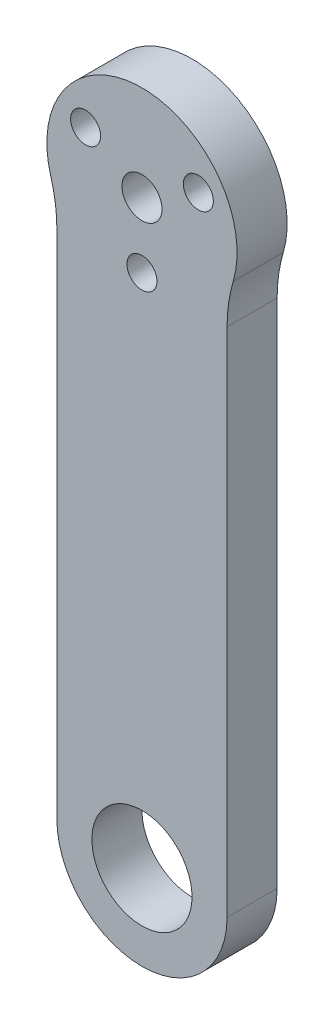
SolidWorks part; units mm, degrees
material "Thornel Mat VMA"
ref_plane "前视基准面" through (0, 0, 0) normal (0, 0, 1) x (1, 0, 0)
ref_plane "上视基准面" through (0, 0, 0) normal (0, 1, 0) x (1, 0, 0)
ref_plane "右视基准面" through (0, 0, 0) normal (1, 0, 0) x (0, 0, -1)
sketch "草图1" plane through (0, 0, 0) normal (0, 0, 1) x (1, 0, 0)
  line L0 (0, 0) -> (0, -58) construction
  line L1 (-8.5, -58) -> (-8.5, -4.2426)
  line L2 (8.5, -58) -> (8.5, -4.2426)
  arc A0 (8.5, -4.2426) -> (-8.5, -4.2426) centre (0, 0) ccw
  arc A1 (-8.5, -58) -> (8.5, -58) centre (0, -58) ccw
  circle A2 centre (-5.6292, 3.25) radius 1.5
  circle A5 centre (0, 0) radius 2
  circle A6 centre (0, -58) radius 5
  circle A8 centre (0, 0) radius 6.5 construction
  circle A16 centre (5.6292, 3.25) radius 1.5
  circle A17 centre (0, -6.5) radius 1.5
  point P12 (-11.935, 7.3181)
  point P13 (0, -14)
  dimension "D2" = 17
  dimension "D4" = 3
  dimension "D7" = 4
  dimension "D8" = 10
  dimension "D9" = 3
  dimension "D6" = 3
  dimension "D5" = 13
  dimension "D3" = 58
extrude "凸台-拉伸1" add sketch "草图1" along normal blind 5
fillet "圆角1" radius 15 2 edges at (-8.5, -4.2426, 2.5) (8.5, -4.2426, 2.5)
